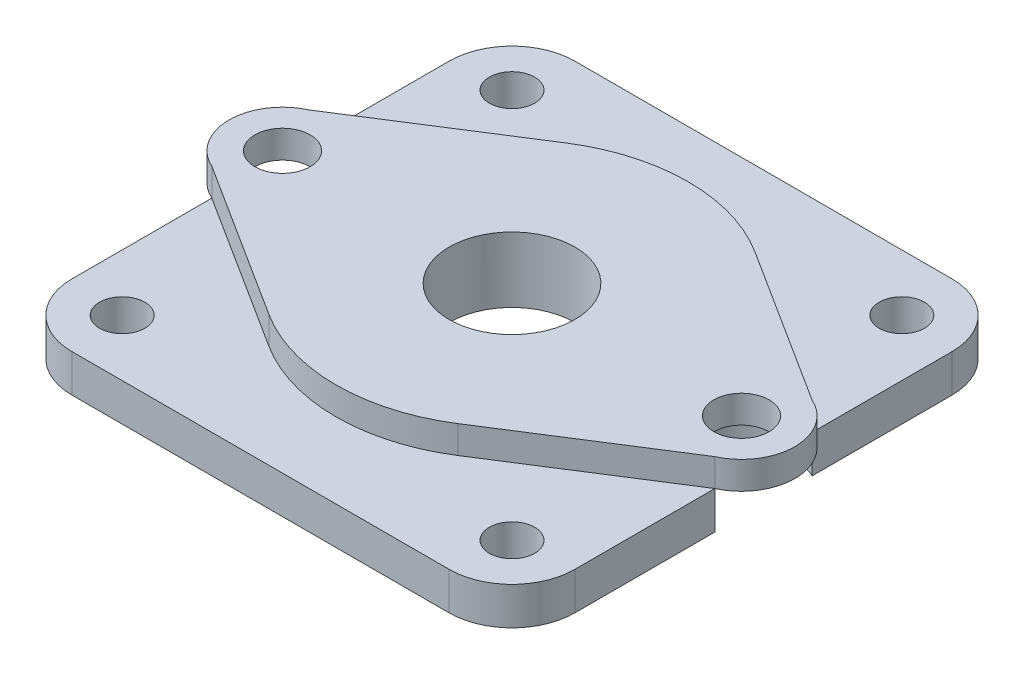
SolidWorks part; units mm, degrees
ref_plane "前视基准面" through (0, 0, 0) normal (0, 0, 1) x (1, 0, 0)
ref_plane "上视基准面" through (0, 0, 0) normal (0, 1, 0) x (1, 0, 0)
ref_plane "右视基准面" through (0, 0, 0) normal (1, 0, 0) x (0, 0, -1)
sketch "草图1" plane through (0, 0, 0) normal (0, 1, 0) x (1, 0, 0)
  line L0 (20, -3.873) -> (20, -15)
  line L1 (-15, 20) -> (15, 20)
  line L2 (-20, 15) -> (-20, 3.873)
  line L3 (-15, -20) -> (15, -20)
  line L4 (20, 15) -> (20, 3.873)
  line L5 (-20, -3.873) -> (-20, -15)
  circle A0 centre (-15.5, 15.5) radius 1.8
  circle A1 centre (15.5, 15.5) radius 1.8
  circle A2 centre (-15.5, -15.5) radius 1.8
  circle A3 centre (15.5, -15.5) radius 1.8
  arc A4 (-20, 15) -> (-15, 20) centre (-15, 15) cw
  arc A5 (20, 15) -> (15, 20) centre (15, 15) ccw
  arc A6 (15, -20) -> (20, -15) centre (15, -15) ccw
  arc A7 (-20, -15) -> (-15, -20) centre (-15, -15) ccw
  circle A8 centre (0, 0) radius 5
  arc A9 (-20, -3.873) -> (-20, 3.873) centre (-18.25, 0) ccw
  arc A10 (20, 3.873) -> (20, -3.873) centre (18.25, 0) ccw
  dimension "D1" = 5
  dimension "D2" = 5
  dimension "D3" = 5
  dimension "D4" = 5
extrude "凸台-拉伸1" add sketch "草图1" along normal blind 3
sketch "草图2" plane through (0, 3, 0) normal (0, 1, 0) x (1, 0, 0)
  line L0 (-20, 3.873) -> (-7.5123, 11.8138)
  line L1 (-20, -3.873) -> (-7.5123, -11.8138)
  line L2 (20, 3.873) -> (7.5123, 11.8138)
  line L3 (20, -3.873) -> (7.5123, -11.8138)
  line L4 (-20, 15) -> (-20, 3.873) construction
  line L5 (-20, 3.873) -> (-20, 1.3332)
  line L6 (-20, -3.873) -> (-20, -1.3332)
  line L7 (20, 3.873) -> (20, 1.3332)
  line L8 (20, -1.3332) -> (20, -3.873)
  arc A0 (-7.5123, -11.8138) -> (7.5123, -11.8138) centre (0, 0) ccw
  arc A1 (7.5123, 11.8138) -> (-7.5123, 11.8138) centre (0, 0) ccw
  arc A2 (20, 1.3332) -> (20, -1.3332) centre (18.25, 0) ccw
  arc A3 (-20, -1.3332) -> (-20, 1.3332) centre (-18.25, 0) ccw
  arc A4 (-20, -3.873) -> (-20, 3.873) centre (-18.25, 0) ccw construction
extrude "凸台-拉伸2" add sketch "草图2" along normal blind 2.2
sketch "草图3" plane through (0, 3, 0) normal (0, -1, 0) x (1, 0, 0)
  circle A0 centre (0, 0) radius 5
extrude "切除-拉伸1" cut sketch "草图3" against normal blind 2.2
sketch "草图4" plane through (0, 3, 0) normal (0, -1, 0) x (1, 0, 0)
  line L0 (20, 3.873) -> (20, 1.3332)
  line L1 (20, -1.3332) -> (20, -3.873)
  arc A0 (20, -1.3332) -> (20, 1.3332) centre (18.25, 0) ccw
  arc A1 (20, -3.873) -> (20, 3.873) centre (18.25, 0) ccw
extrude "凸台-拉伸4" add sketch "草图4" against normal blind 2.2
sketch "草图5" plane through (0, 3, 0) normal (0, -1, 0) x (1, 0, 0)
  line L0 (-20, 3.873) -> (-20, 1.3332)
  line L1 (-20, -1.3332) -> (-20, -3.873)
  arc A0 (-20, 1.3332) -> (-20, -1.3332) centre (-18.25, 0) ccw
  arc A1 (-20, 3.873) -> (-20, -3.873) centre (-18.25, 0) ccw
extrude "凸台-拉伸5" add sketch "草图5" against normal blind 2.2
